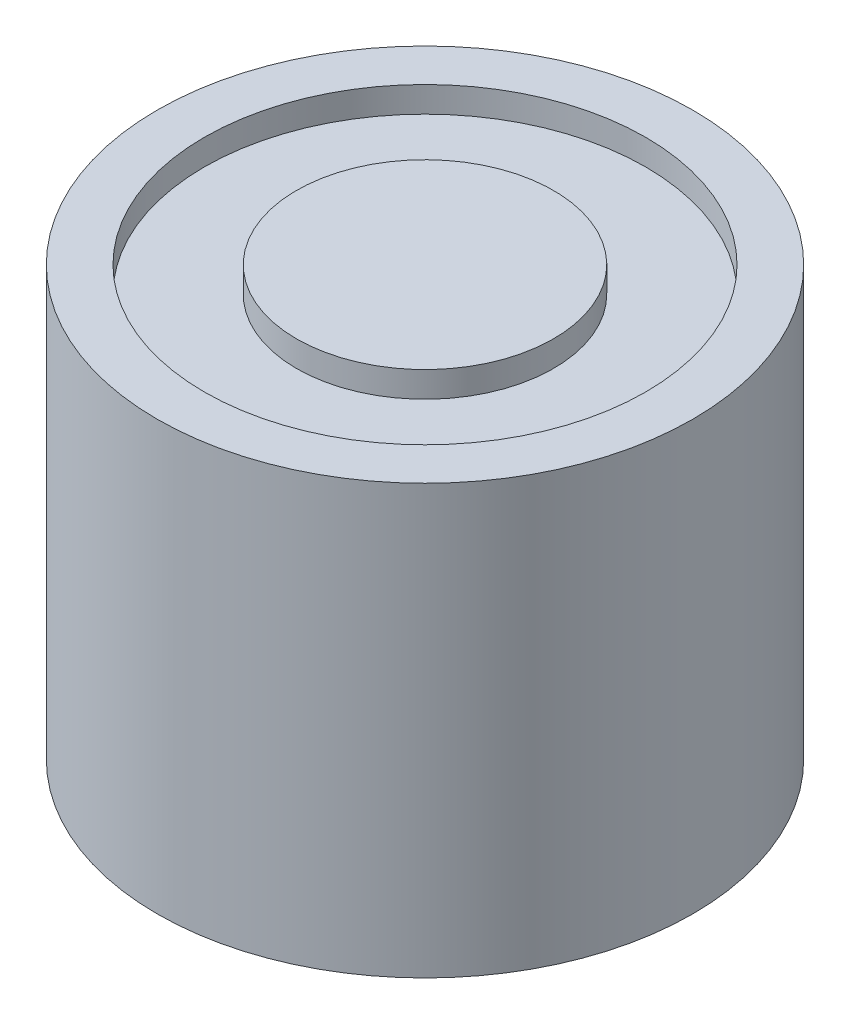
SolidWorks part; units mm, degrees
ref_plane "Front Plane" through (0, 0, 0) normal (0, 0, 1) x (1, 0, 0)
ref_plane "Top Plane" through (0, 0, 0) normal (0, 1, 0) x (1, 0, 0)
ref_plane "Right Plane" through (0, 0, 0) normal (1, 0, 0) x (0, 0, -1)
sketch "Sketch2" plane through (0, 0, 0) normal (0, 1, 0) x (1, 0, 0)
  circle A0 centre (0, 0) radius 12.5
  dimension "D1" = 25
extrude "Boss-Extrude1" add sketch "Sketch2" along normal blind 20
sketch "Sketch3" plane through (0, 20, 0) normal (0, 1, 0) x (1, 0, 0)
  circle A0 centre (0, 0) radius 6
  circle A1 centre (0, 0) radius 10.3
  dimension "D1" = 12
  dimension "D2" = 20.6
extrude "Cut-Extrude1" cut sketch "Sketch3" against normal blind 1.2
sketch "Sketch4" plane through (0, 0, 0) normal (0, -1, 0) x (1, 0, 0)
  circle A0 centre (0, 0) radius 2
  dimension "D1" = 4
extrude "Cut-Extrude2" cut sketch "Sketch4" against normal blind 12
